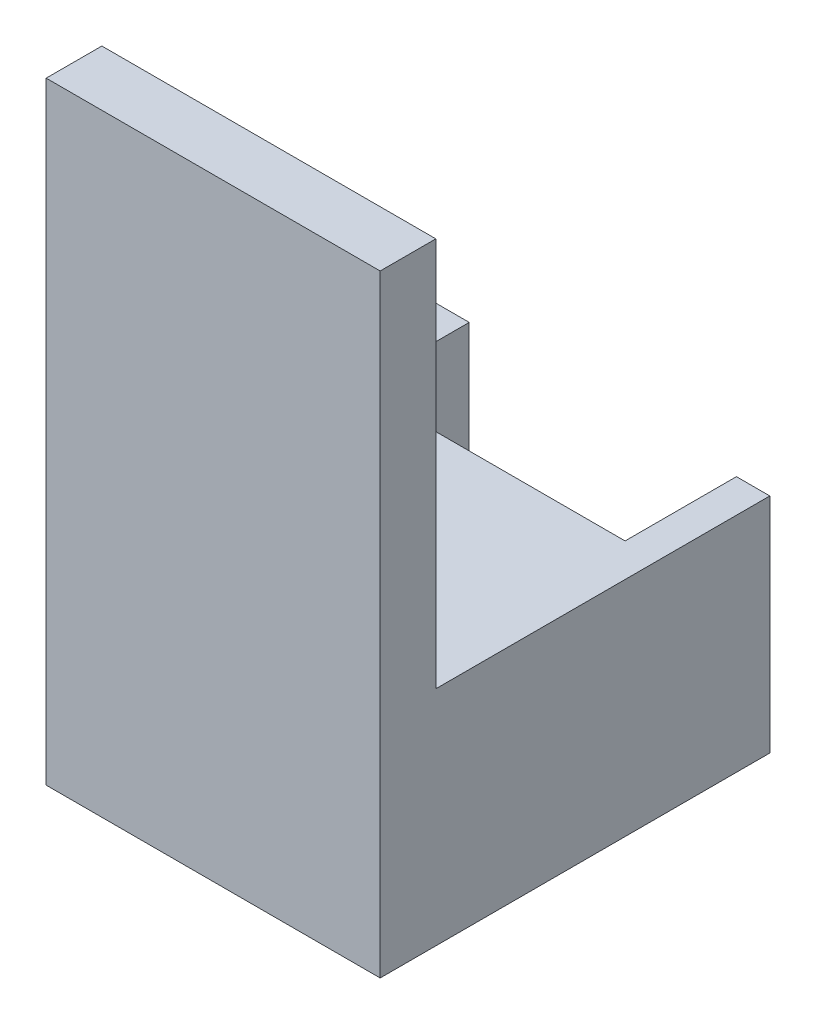
SolidWorks part; units mm, degrees
ref_plane "Front Plane" through (0, 0, 0) normal (0, 0, 1) x (1, 0, 0)
ref_plane "Top Plane" through (0, 0, 0) normal (0, 1, 0) x (1, 0, 0)
ref_plane "Right Plane" through (0, 0, 0) normal (1, 0, 0) x (0, 0, -1)
sketch "Sketch1" plane through (0, 0, 0) normal (0, 1, 0) x (1, 0, 0)
  line L0 (27, 35) -> (30, 35)
  line L1 (0, 0) -> (30, 0)
  line L2 (0, 0) -> (0, 35)
  line L3 (0, 35) -> (3, 35)
  line L4 (30, 0) -> (30, 35)
  line L6 (3, 35) -> (3, 25)
  line L7 (3, 25) -> (27, 25)
  line L8 (27, 35) -> (27, 25)
  point P9 (15, 25)
  point P10 (15, 0)
  dimension "D1" = 30
  dimension "D2" = 35
  dimension "D3" = 3
  dimension "D4" = 25
extrude "Boss-Extrude1" add sketch "Sketch1" along normal blind 20
sketch "Sketch4" plane through (0, 20, 0) normal (0, 1, 0) x (1, 0, 0)
  line L0 (30, 0) -> (30, 35) construction
  line L1 (0, 0) -> (30, 0)
  line L2 (0, 0) -> (0, 5)
  line L3 (0, 5) -> (30, 5)
  line L4 (30, 0) -> (30, 5)
  dimension "D1" = 5
extrude "Boss-Extrude3" add sketch "Sketch4" along normal blind 35
